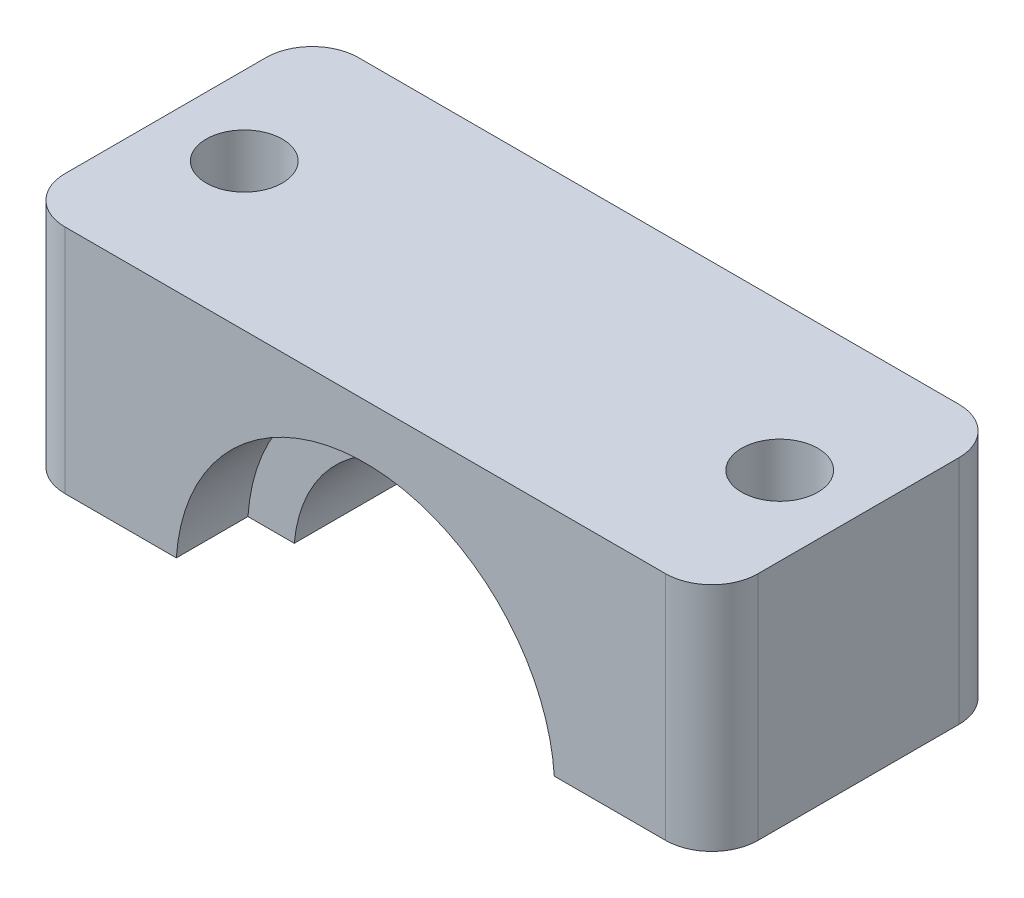
SolidWorks part; units mm, degrees
ref_plane "Front Plane" through (0, 0, 0) normal (0, 0, 1) x (1, 0, 0)
ref_plane "Top Plane" through (0, 0, 0) normal (0, 1, 0) x (1, 0, 0)
ref_plane "Right Plane" through (0, 0, 0) normal (1, 0, 0) x (0, 0, -1)
sketch "Sketch1" plane through (0, 0, 0) normal (0, 1, 0) x (1, 0, 0)
  line L1 (-15, -6.35) -> (15, -6.35)
  line L2 (-15, -6.35) -> (-15, 6.35)
  line L3 (-15, 6.35) -> (15, 6.35)
  line L4 (15, -6.35) -> (15, 6.35)
  line L5 (-15, -6.35) -> (15, 6.35) construction
  line L6 (-15, 6.35) -> (15, -6.35) construction
  point P0 (0, 0)
  dimension "D1" = 12.7
  dimension "D2" = 30
extrude "Boss-Extrude1" add sketch "Sketch1" along normal blind 10
sketch "Sketch2" plane through (0, 0, -6.35) normal (0, 0, -1) x (-1, 0, 0)
  circle A1 centre (0, -0.55) radius 8.2
  circle A2 centre (0, -0.55) radius 8.2
  dimension "D1" = 0
extrude "Cut-Extrude1" cut sketch "Sketch2" against normal blind 3.8 contours A2
sketch "Sketch3" plane through (0, 0, 6.35) normal (0, 0, 1) x (1, 0, 0)
  circle A1 centre (0, -0.55) radius 8.2
  arc A2 (8.1815, 0) -> (-8.1815, 0) centre (0, -0.55) ccw construction
extrude "Cut-Extrude2" cut sketch "Sketch3" against normal blind 3.1
sketch "Sketch4" plane through (0, 0, 3.25) normal (0, 0, 1) x (1, 0, 0)
  circle A1 centre (0, -0.55) radius 6.2
  circle A2 centre (0, -0.55) radius 6.2
  dimension "D1" = 0
extrude "Cut-Extrude3" cut sketch "Sketch4" against normal through all both and the other way through all
fillet "Fillet1" radius 2 4 edges at (15, 5, -6.35) (15, 5, 6.35) (-15, 5, 6.35) (-15, 5, -6.35)
sketch "Sketch5" plane through (0, 0, 0) normal (0, -1, 0) x (1, 0, 0)
  line L0 (-8.1815, 6.35) -> (-15, 6.35) construction
  line L1 (-15, 6.35) -> (-15, -6.35) construction
  line L2 (-15, -6.35) -> (-8.1815, -6.35) construction
  line L3 (-15, -4.35) -> (-15, 4.35) construction
  line L4 (-8.1815, 6.35) -> (-15, -6.35) construction
  circle A0 centre (-11.5908, 0) radius 1.65
  dimension "D1" = 3.3
extrude "Cut-Extrude4" cut sketch "Sketch5" against normal through all both and the other way through all
mirror "Mirror1" about plane through (0, 0, 0) normal (1, 0, 0) of "Cut-Extrude4"
